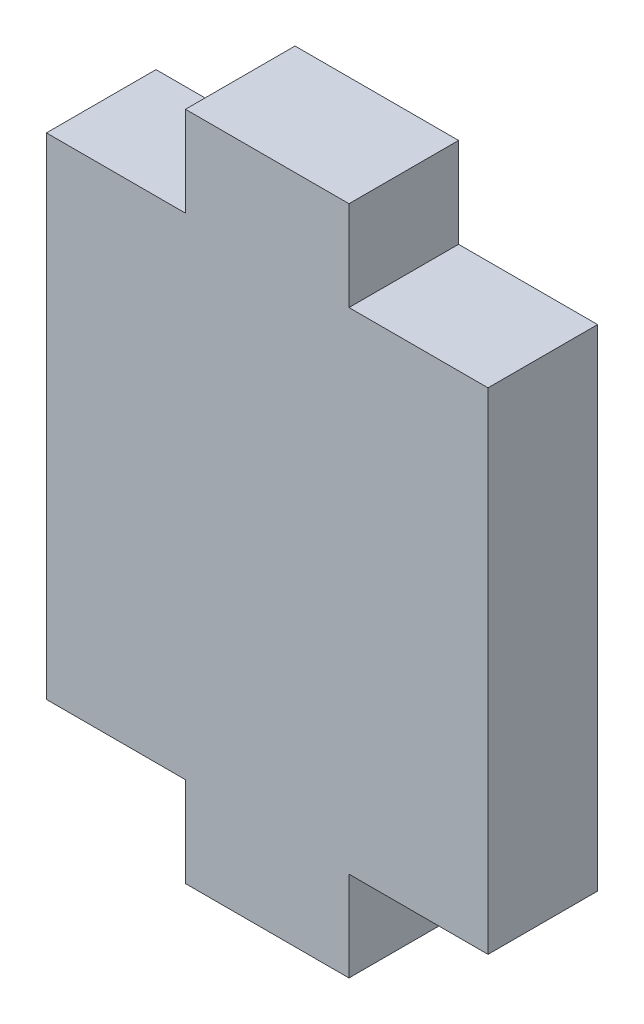
SolidWorks part; units mm, degrees
ref_plane "Front Plane" through (0, 0, 0) normal (0, 0, 1) x (1, 0, 0)
ref_plane "Top Plane" through (0, 0, 0) normal (0, 1, 0) x (1, 0, 0)
ref_plane "Right Plane" through (0, 0, 0) normal (1, 0, 0) x (0, 0, -1)
sketch "Sketch1" plane through (0, 0, 0) normal (0, 0, 1) x (1, 0, 0)
  line L0 (5, -15) -> (13.5, -15)
  line L1 (-13.5, -15) -> (-5, -15)
  line L2 (-13.5, -15) -> (-13.5, 15)
  line L3 (-13.5, 15) -> (-5, 15)
  line L4 (13.5, -15) -> (13.5, 15)
  line L5 (-13.5, -15) -> (13.5, 15) construction
  line L6 (-13.5, 15) -> (13.5, -15) construction
  line L8 (5, 15) -> (5, 20.5)
  line L9 (5, 20.5) -> (-5, 20.5)
  line L10 (-5, 15) -> (-5, 20.5)
  line L12 (5, -15) -> (5, -20.5)
  line L13 (5, -20.5) -> (-5, -20.5)
  line L14 (-5, -15) -> (-5, -20.5)
  line L15 (5, 15) -> (13.5, 15)
  line L16 (0, -25.7964) -> (0, 25.7271) construction
  line L17 (-35.3878, 0) -> (40.7202, 0) construction
  point P0 (0, 0)
  point P16 (0, 20.5)
  point P17 (0, -20.5)
  point P20 (13.5, 0)
  point P21 (-13.5, 0)
  dimension "D1" = 30
  dimension "D2" = 10
  dimension "D3" = 8.5
  dimension "D4" = 5.5
extrude "Boss-Extrude1" add sketch "Sketch1" along normal blind 6.7
